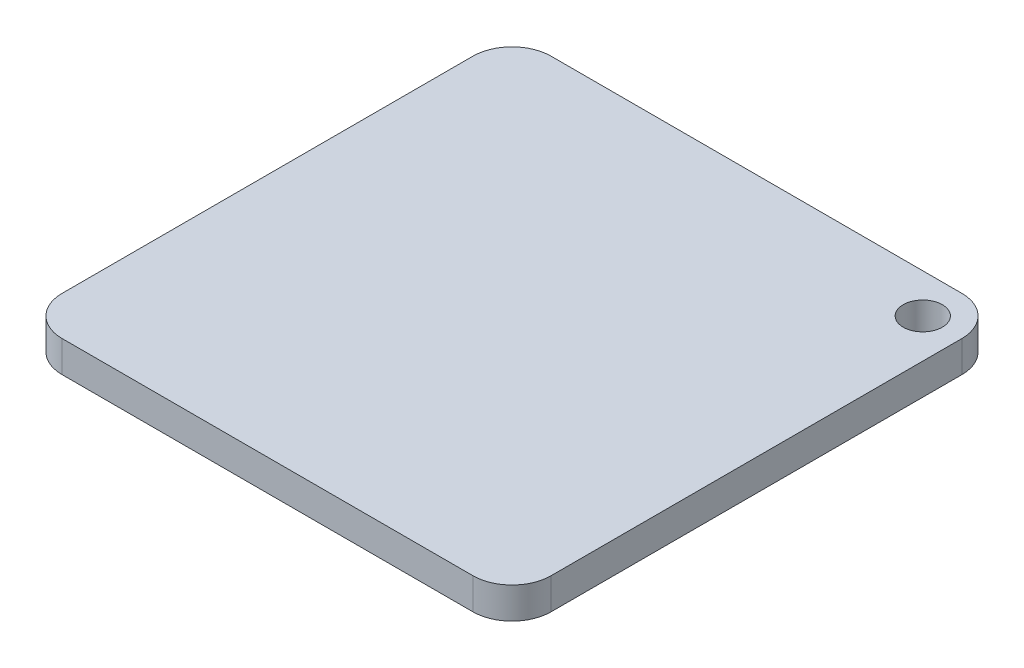
SolidWorks part; units mm, degrees
ref_plane "前视基准面" through (0, 0, 0) normal (0, 0, 1) x (1, 0, 0)
ref_plane "上视基准面" through (0, 0, 0) normal (0, 1, 0) x (1, 0, 0)
ref_plane "右视基准面" through (0, 0, 0) normal (1, 0, 0) x (0, 0, -1)
other "Configuration Table"
sketch "草图1" plane through (0, 0, 0) normal (0, 1, 0) x (1, 0, 0)
  line L1 (-10.5, 12.5) -> (10.5, 12.5)
  line L2 (-12.5, 10.5) -> (-12.5, -10.5)
  line L3 (-10.5, -12.5) -> (10.5, -12.5)
  line L4 (12.5, 10.5) -> (12.5, -10.5)
  line L5 (-12.5, 12.5) -> (12.5, -12.5) construction
  line L6 (-12.5, -12.5) -> (12.5, 12.5) construction
  arc A0 (-10.5, 12.5) -> (-12.5, 10.5) centre (-10.5, 10.5) ccw
  arc A1 (12.5, 10.5) -> (10.5, 12.5) centre (10.5, 10.5) ccw
  arc A2 (-12.5, -10.5) -> (-10.5, -12.5) centre (-10.5, -10.5) ccw
  arc A3 (10.5, -12.5) -> (12.5, -10.5) centre (10.5, -10.5) ccw
  circle A4 centre (10.5, 10.5) radius 1
  point P0 (0, 0)
  dimension "D3" = 4
  dimension "D4" = 4
  dimension "D5" = 4
  dimension "D6" = 4
  dimension "D7" = 2
  dimension "D1" = 25
  dimension "D2" = 25
  dimension "D8" = 25
  dimension "D9" = 25
  dimension "D10" = 12.5
  dimension "D11" = 12.5
extrude "凸台-拉伸1" add sketch "草图1" along normal blind 1.6
